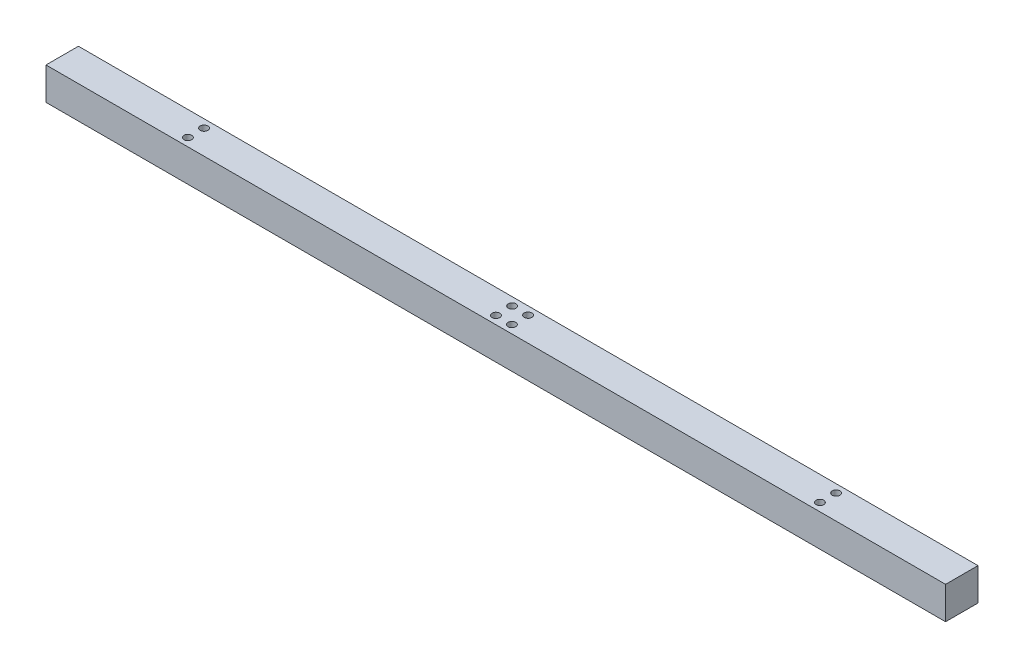
SolidWorks part; units mm, degrees
material "2018 Alloy"
ref_plane "Front Plane" through (0, 0, 0) normal (0, 0, 1) x (1, 0, 0)
ref_plane "Top Plane" through (0, 0, 0) normal (0, 1, 0) x (1, 0, 0)
ref_plane "Right Plane" through (0, 0, 0) normal (1, 0, 0) x (0, 0, -1)
sketch "Sketch2" plane through (0, 0, 0) normal (1, 0, 0) x (0, 0, -1)
  line L1 (-5, -5) -> (5, -5)
  line L2 (-5, -5) -> (-5, 5)
  line L3 (-5, 5) -> (5, 5)
  line L4 (5, -5) -> (5, 5)
  line L5 (-5, -5) -> (5, 5) construction
  line L6 (-5, 5) -> (5, -5) construction
  point P0 (0, 0)
  dimension "D1" = 10
  dimension "D2" = 10
extrude "Boss-Extrude1" add sketch "Sketch2" along normal blind 277.4
hole_wizard "3/32 (0.09375) Diameter Hole3" positions "Sketch10" profile "Sketch9" hole size "3/32" standard "ANSI Inch"
sketch "Sketch10" plane through (0, -5, 0) normal (0, -1, 0) x (-1, 0, 0)
  line L0 (-277.4, 5) -> (-277.4, -5) construction
  point P0 (-5.85, 0)
  point P2 (-271.55, 0)
  point P6 (-277.4, 0)
  dimension "D1" = 5.85
  dimension "D2" = 5.85
sketch "Sketch9" plane through (5.85, -5, 0) normal (1, 0, 0) x (0, 0, -1)
  line L0 (0, 0) -> (0, 5.7154)
  line L1 (0, 5.7154) -> (1.1906, 5)
  line L2 (1.1906, 5) -> (1.1906, 0)
  line L5 (1.1906, 0) -> (0, 0)
  line L10 (0, 5.7154) -> (-1.1906, 5) construction
  line L11 (0, -6.35) -> (0, 107.95) construction
  dimension "Hole Dia." = 2.3812
  dimension "Hole Depth" = 5
  dimension "Drill Angle" = 118
sketch "Sketch11" plane through (0, 5, 0) normal (0, 1, 0) x (1, 0, 0)
  line L0 (277.4, 5) -> (0, 5) construction
  line L1 (0, 5) -> (0, -5) construction
  line L2 (0, 0) -> (290.1459, 0) construction
  line L3 (138.7, 5) -> (138.7, -14.0489) construction
  circle A0 centre (41.25, 2.5) radius 1.25
  circle A1 centre (136.25, 2.5) radius 1.25
  circle A2 centre (141.15, 2.5) radius 1.25
  circle A3 centre (236.15, 2.5) radius 1.25
  circle A4 centre (236.15, -2.5) radius 1.25
  circle A5 centre (141.15, -2.5) radius 1.25
  circle A6 centre (136.25, -2.5) radius 1.25
  circle A7 centre (41.25, -2.5) radius 1.25
  dimension "D1" = 2.5
  dimension "D2" = 2.5
  dimension "D3" = 41.25
  dimension "D4" = 2
hole_wizard "3/32 (0.09375) Diameter Hole5" positions "Sketch15" profile "Sketch14" hole size "3/32" standard "ANSI Inch"
sketch "Sketch15" plane through (0, 5, 0) normal (0, 1, 0) x (1, 0, 0)
  point P0 (41.25, 2.5)
  point P3 (41.25, -2.5)
  point P6 (136.25, 2.5)
  point P9 (136.25, -2.5)
  point P12 (141.15, -2.5)
  point P15 (141.15, 2.5)
  point P18 (236.15, -2.5)
  point P21 (236.15, 2.5)
sketch "Sketch14" plane through (41.25, 5, -2.5) normal (1, 0, 0) x (0, 0, 1)
  line L0 (0, 0) -> (0, 5.7154)
  line L1 (0, 5.7154) -> (1.1906, 5)
  line L2 (1.1906, 5) -> (1.1906, 0)
  line L5 (1.1906, 0) -> (0, 0)
  line L10 (0, 5.7154) -> (-1.1906, 5) construction
  line L11 (0, -6.35) -> (0, 107.95) construction
  dimension "Hole Dia." = 2.3812
  dimension "Hole Depth" = 5
  dimension "Drill Angle" = 118
